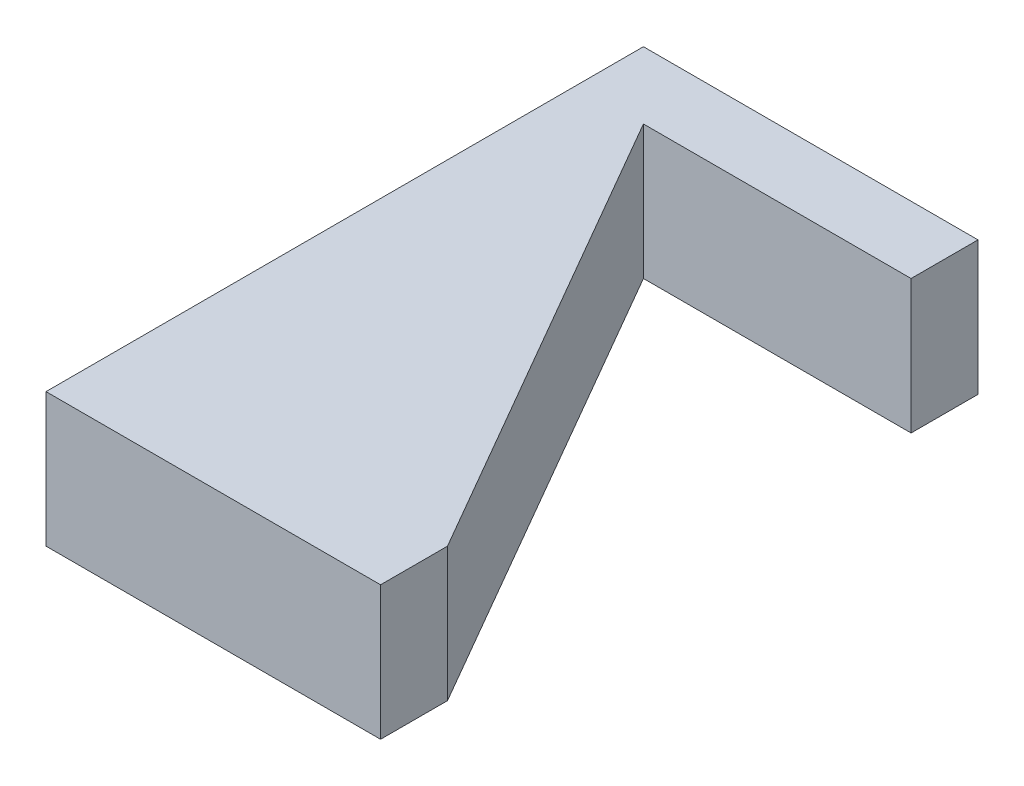
SolidWorks part; units mm, degrees
ref_plane "Přední rovina" through (0, 0, 0) normal (0, 0, 1) x (1, 0, 0)
ref_plane "Horní rovina" through (0, 0, 0) normal (0, 1, 0) x (1, 0, 0)
ref_plane "Pravá rovina" through (0, 0, 0) normal (1, 0, 0) x (0, 0, -1)
sketch "Sketch1" plane through (0, 0, 0) normal (0, 1, 0) x (1, 0, 0)
  line L0 (0, 0) -> (0, -89.282)
  line L1 (0, -89.282) -> (50, -89.282)
  line L2 (50, -89.282) -> (50, -79.282)
  line L5 (10, -10) -> (50, -10)
  line L6 (50, -10) -> (50, 0)
  line L7 (50, 0) -> (0, 0)
  line L8 (10, -10) -> (50, -79.282)
  dimension "D1" = 10
  dimension "D2" = 10
  dimension "D3" = 40
  dimension "D4" = 60
  dimension "D5" = 10
extrude "Boss-Extrude1" add sketch "Sketch1" along normal blind 20 contours L8 L2 L1 L0 L7 L6 L5
equation "\"Angle\"= 60"
equation "\"L\"= 40"
equation "\"D3@Sketch1\"=\"L\""
equation "\"D4@Sketch1\"=\"Angle\""
